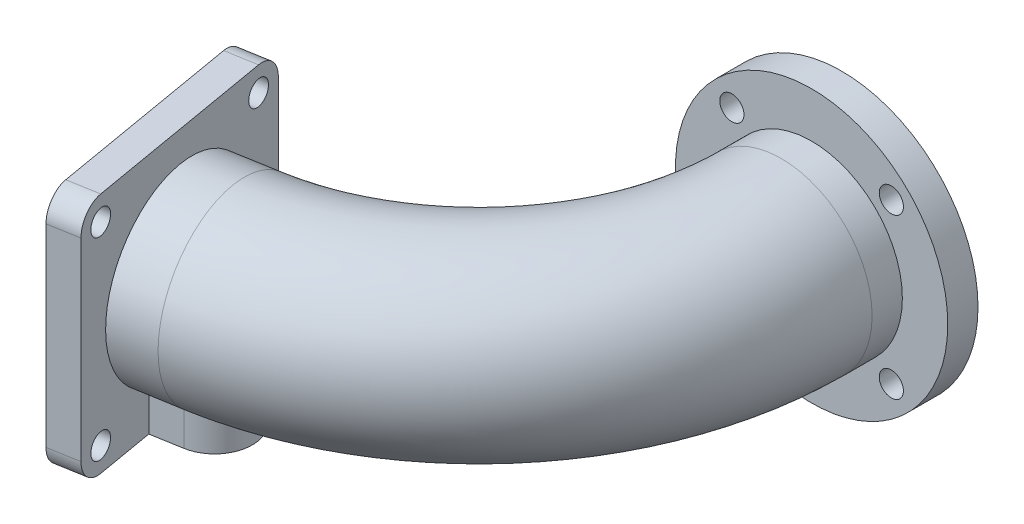
SolidWorks part; units mm, degrees
ref_plane "정면" through (0, 0, 0) normal (0, 0, 1) x (1, 0, 0)
ref_plane "윗면" through (0, 0, 0) normal (0, 1, 0) x (1, 0, 0)
ref_plane "우측면" through (0, 0, 0) normal (1, 0, 0) x (0, 0, -1)
sketch "Sketch1" plane through (0, 0, 0) normal (0, 0, 1) x (1, 0, 0)
  line L0 (0, 0) -> (51.3814, 0) construction
  line L1 (0, 0) -> (32.0187, 32.0187) construction
  circle A0 centre (0, 0) radius 22.5
  circle A1 centre (0, 0) radius 15
  circle A2 centre (13.1777, 13.1777) radius 2
  circle A3 centre (13.1777, -13.1777) radius 2
  circle A4 centre (-13.1777, -13.1777) radius 2
  circle A5 centre (-13.1777, 13.1777) radius 2
  point P17 (0, 0)
  dimension "D1" = 45
  dimension "D2" = 30
  dimension "D4" = 4
  dimension "D3" = 45
  dimension "D5" = 4
extrude "Boss-Extrude1" add sketch "Sketch1" along normal blind 5
sketch "Sketch3" plane through (0, 0, 0) normal (0, 1, 0) x (1, 0, 0)
  line L0 (-50, -10) -> (0, -10) construction
  line L1 (0, -10) -> (0, 2.5)
  line L2 (-41.5016, -59.2725) -> (-53.8198, -61.3971)
  arc A0 (0, -10) -> (-41.5016, -59.2725) centre (-50, -10) cw
  dimension "D1" = 50
  dimension "D2" = 70
  dimension "D3" = 12.5
  dimension "D4" = 2.5
  dimension "D5" = 0
  dimension "D6" = 12.5
ref_plane "Plane1" through (-53.8198, 0, 61.3971) normal (-0.9854, 0, 0.17) x (0.17, 0, 0.9854)
sketch "Sketch4" plane through (-53.8198, 0, 61.3971) normal (-0.9854, 0, 0.17) x (0.17, 0, 0.9854)
  circle A0 centre (0, 0) radius 15
  circle A1 centre (0, 0) radius 10
  dimension "D1" = 30
  dimension "D2" = 20
sweep "Sweep1" add profiles "Sketch4" path "Sketch3"
ref_plane "Plane2" through (-62.5486, 0, 10.7882) normal (-0.9854, 0, 0.17) x (0.17, 0, 0.9854)
sketch "Sketch5" plane through (-62.5486, 0, 10.7882) normal (-0.9854, 0, 0.17) x (0.17, 0, 0.9854)
  line L1 (31.3561, 20) -> (71.3561, 20)
  line L2 (31.3561, 20) -> (31.3561, -20)
  line L3 (31.3561, -20) -> (71.3561, -20)
  line L4 (71.3561, 20) -> (71.3561, -20)
  line L5 (31.3561, 20) -> (71.3561, -20) construction
  line L6 (31.3561, -20) -> (71.3561, 20) construction
  circle A0 centre (51.3561, 0) radius 10
  circle A1 centre (67.3561, 16) radius 2
  circle A2 centre (35.3561, 16) radius 2
  circle A3 centre (35.3561, -16) radius 2
  circle A4 centre (67.3561, -16) radius 2
  point P0 (51.3561, 0)
  dimension "D3" = 20
  dimension "D4" = 4
  dimension "D7" = 4
  dimension "D8" = 4
  dimension "D1" = 40
  dimension "D2" = 40
  dimension "D5" = 4
  dimension "D6" = 2
  dimension "D9" = 4
  dimension "D10" = 4
extrude "Boss-Extrude2" add sketch "Sketch5" against normal blind 5
fillet "Fillet1" radius 4 4 edges at (-47.9568, -20, 80.6812) (-54.7555, -20, 41.2632) (-47.9568, 20, 80.6812) (-54.7555, 20, 41.2632)
ref_plane "Plane3" through (0, -20, 0) normal (0, -1, 0) x (-1, 0, 0)
sketch "Sketch6" plane through (0, -20, 0) normal (0, -1, 0) x (-1, 0, 0)
  line L0 (48.8925, -60.5472) -> (43.9653, -59.6974)
  line L1 (51.442, -45.7655) -> (46.343, -75.329) construction
  line L2 (48.8925, -60.5472) -> (47.8302, -66.7063)
  line L3 (47.8302, -66.7063) -> (42.903, -65.8565)
  line L4 (49.9548, -54.3882) -> (48.8925, -60.5472)
  line L5 (45.0276, -53.5383) -> (49.9548, -54.3882)
  arc A0 (42.903, -65.8565) -> (45.0276, -53.5383) centre (43.9653, -59.6974) cw
  circle A1 centre (43.9653, -59.6974) radius 3
  dimension "D6" = 6.25
  dimension "D7" = 6
  dimension "D1" = 12.5
  dimension "D2" = 6.25
  dimension "D3" = 5
  dimension "D4" = 5
  dimension "D5" = 5
extrude "Boss-Extrude3" add sketch "Sketch6" against normal blind 7
